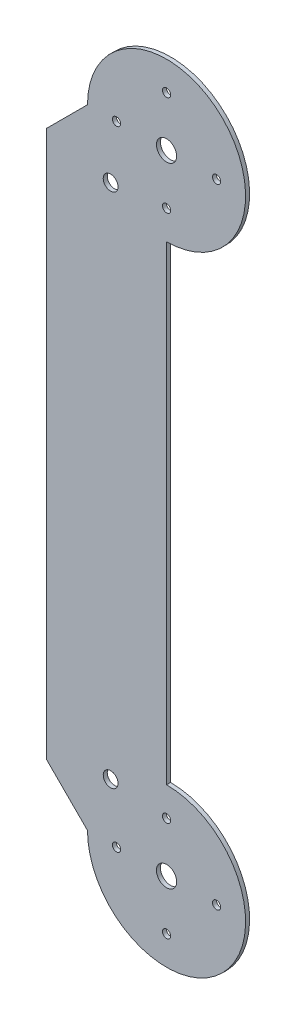
SolidWorks part; units mm, degrees
ref_plane "前视基准面" through (0, 0, 0) normal (0, 0, 1) x (1, 0, 0)
ref_plane "上视基准面" through (0, 0, 0) normal (0, 1, 0) x (1, 0, 0)
ref_plane "右视基准面" through (0, 0, 0) normal (1, 0, 0) x (0, 0, -1)
sketch "草图1" plane through (0, 0, 0) normal (0, 0, 1) x (1, 0, 0)
  line L0 (-80.688, 42.4149) -> (-80.688, -192.5851)
  line L1 (-120.188, 81.9149) -> (-140.688, 61.4149)
  line L18 (-80.688, 81.9149) -> (128.4933, 81.9149) construction
  line L23 (-140.688, -211.5851) -> (-140.688, 61.4149)
  line L42 (-80.688, -75.0851) -> (-140.688, -75.0851) construction
  line L61 (-80.688, 81.9149) -> (-200.2437, -37.6408) construction
  line L62 (-80.688, -232.0851) -> (-200.2437, -112.5293) construction
  line L63 (-80.688, -232.0851) -> (128.4933, -232.0851) construction
  line L65 (-120.188, -232.0851) -> (-140.688, -211.5851)
  circle A0 centre (-80.688, 81.9149) radius 5.05
  circle A1 centre (-80.688, 81.9149) radius 25 construction
  circle A7 centre (-80.688, 56.9149) radius 2.05
  circle A12 centre (-80.688, 81.9149) radius 39.5 construction
  arc A23 (-120.188, 81.9149) -> (-80.688, 42.4149) centre (-80.688, 81.9149) cw
  circle A24 centre (-108.6187, 53.9842) radius 3.7017
  circle A25 centre (-55.688, 81.9149) radius 2.05
  circle A37 centre (-105.688, 81.9149) radius 2.05
  circle A38 centre (-80.688, 106.9149) radius 2.05
  circle A39 centre (-80.688, -232.0851) radius 39.5 construction
  circle A40 centre (-80.688, -232.0851) radius 25 construction
  circle A41 centre (-80.688, -257.0851) radius 2.05
  circle A42 centre (-105.688, -232.0851) radius 2.05
  circle A43 centre (-55.688, -232.0851) radius 2.05
  circle A44 centre (-108.6187, -204.1543) radius 3.7017
  arc A45 (-120.188, -232.0851) -> (-80.688, -192.5851) centre (-80.688, -232.0851) ccw
  circle A46 centre (-80.688, -207.0851) radius 2.05
  circle A47 centre (-80.688, -232.0851) radius 5.05
  dimension "D10" = 10.1
  dimension "D13" = 50
  dimension "D2" = 79
  dimension "D4" = 314
  dimension "D8" = 4.1
  dimension "D3" = 4
  dimension "D5" = 135
  dimension "D6" = 60
extrude "凸台-拉伸1" add sketch "草图1" along normal blind 2
